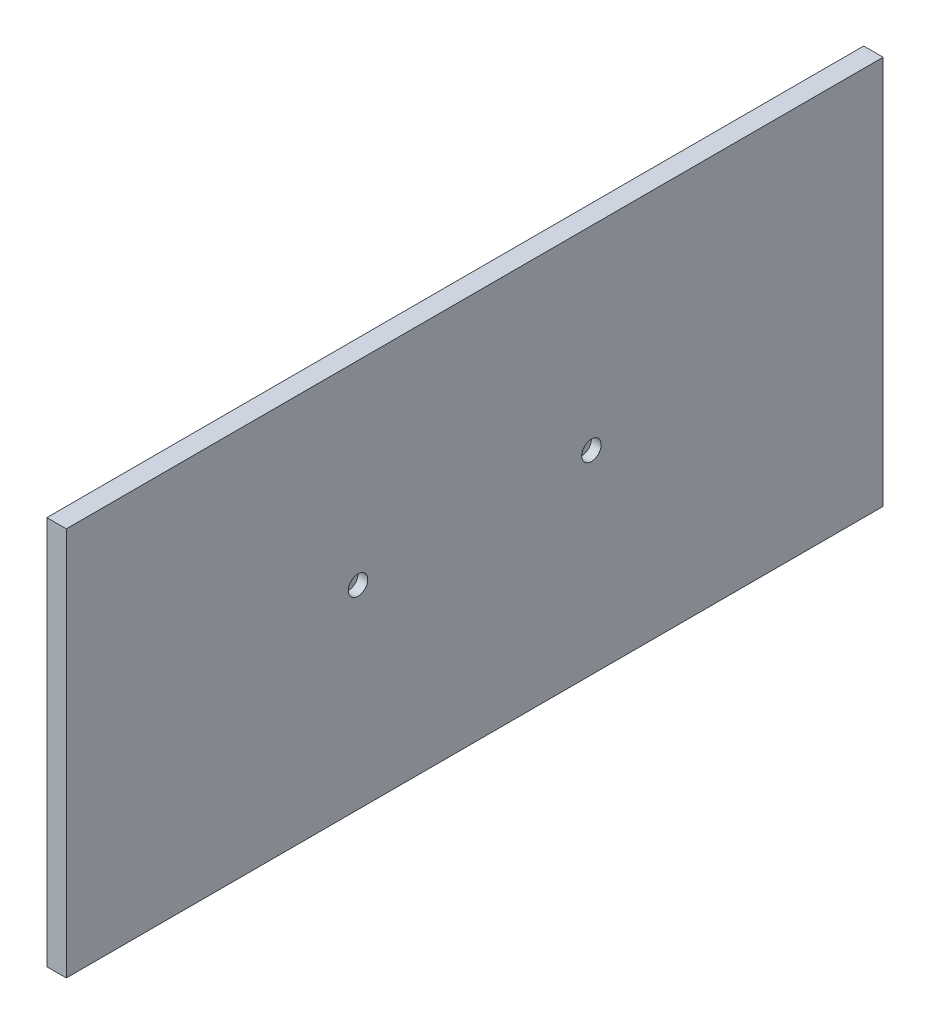
SolidWorks part; units mm, degrees
material "Бук"
ref_plane "Спереди" through (0, 0, 0) normal (0, 0, 1) x (1, 0, 0)
ref_plane "Сверху" through (0, 0, 0) normal (0, 1, 0) x (1, 0, 0)
ref_plane "Справа" through (0, 0, 0) normal (1, 0, 0) x (0, 0, -1)
sketch "Эскиз1" plane through (0, 0, 0) normal (1, 0, 0) x (0, 0, -1)
  line L1 (0, 0) -> (420, 0)
  line L2 (0, 0) -> (0, 200)
  line L3 (0, 200) -> (420, 200)
  line L4 (420, 0) -> (420, 200)
  dimension "D1" = 200
  dimension "D2" = 420
extrude "Бобышка-Вытянуть1" add sketch "Эскиз1" along normal blind 10
sketch "Эскиз2" plane through (10, 0, 0) normal (1, 0, 0) x (0, 0, -1)
  line L0 (210, 200) -> (210, 0) construction
  line L1 (420, 200) -> (0, 200) construction
  line L2 (0, 0) -> (420, 0) construction
  line L3 (0, 100) -> (420, 100) construction
  line L4 (0, 200) -> (0, 0) construction
  line L5 (420, 0) -> (420, 200) construction
  circle A0 centre (150, 100) radius 5
  circle A1 centre (270, 100) radius 5
  dimension "D1" = 10
  dimension "D2" = 10
  dimension "D3" = 60
  dimension "D4" = 60
extrude "Вырез-Вытянуть1" cut sketch "Эскиз2" against normal blind 5
